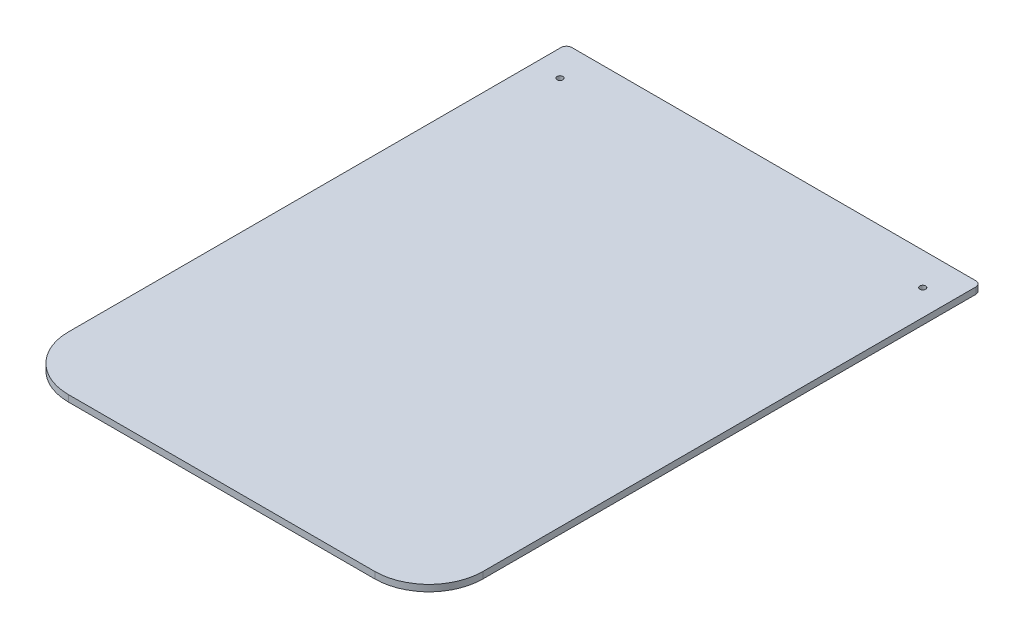
SolidWorks part; units mm, degrees
ref_plane "Front Plane" through (0, 0, 0) normal (0, 0, 1) x (1, 0, 0)
ref_plane "Top Plane" through (0, 0, 0) normal (0, 1, 0) x (1, 0, 0)
ref_plane "Right Plane" through (0, 0, 0) normal (1, 0, 0) x (0, 0, -1)
sketch "Sketch1" plane through (0, 0, 0) normal (0, 1, 0) x (1, 0, 0)
  line L1 (-191.5, 255) -> (191.5, 255)
  line L2 (-191.5, 255) -> (-191.5, -255)
  line L3 (-191.5, -255) -> (191.5, -255)
  line L4 (191.5, 255) -> (191.5, -255)
  line L5 (-191.5, 255) -> (191.5, -255) construction
  line L6 (-191.5, -255) -> (191.5, 255) construction
  point P0 (0, 0)
  dimension "D1" = 510
  dimension "D2" = 383
extrude "Boss-Extrude1" add sketch "Sketch1" along normal blind 6
sketch "Sketch2" plane through (0, 0, 0) normal (0, -1, 0) x (1, 0, 0)
  line L0 (191.5, -255) -> (-191.5, -255) construction
  line L1 (-191.5, -255) -> (-191.5, 255) construction
  line L2 (191.5, 255) -> (191.5, -255) construction
  circle A0 centre (-167.5, -225) radius 2.7
  circle A1 centre (167.5, -225) radius 2.7
  dimension "D3" = 5.4
  dimension "D6" = 5.4
  dimension "D1" = 30
  dimension "D2" = 24
  dimension "D4" = 24
  dimension "D5" = 30
extrude "Cut-Extrude1" cut sketch "Sketch2" against normal through all
fillet "Fillet1" radius 50 2 edges at (-191.5, 3, 255) (191.5, 3, 255)
fillet "Fillet2" radius 5 2 edges at (191.5, 3, -255) (-191.5, 3, -255)
